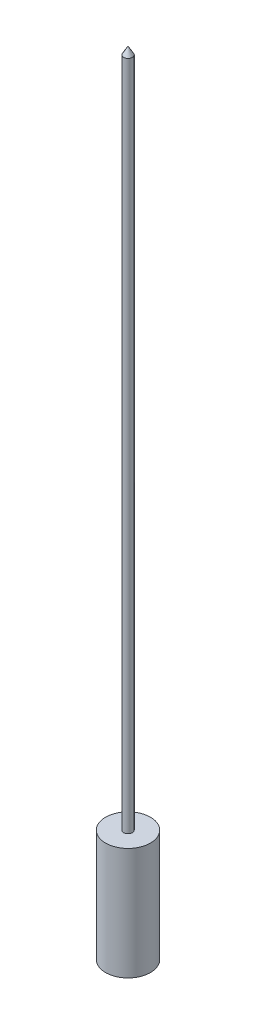
SolidWorks part; units mm, degrees
ref_plane "Front Plane" through (0, 0, 0) normal (0, 0, 1) x (1, 0, 0)
ref_plane "Top Plane" through (0, 0, 0) normal (0, 1, 0) x (1, 0, 0)
ref_plane "Right Plane" through (0, 0, 0) normal (1, 0, 0) x (0, 0, -1)
sketch "Sketch2" plane through (0, 0, 0) normal (1, 0, 0) x (0, 0, -1)
  line L0 (0, 0) -> (0, 76)
  line L1 (0, 76) -> (0, 76.866)
  line L2 (0, 0) -> (0.5, 0)
  line L3 (0.5, 0) -> (0.5, 76)
  line L4 (0.5, 76) -> (0, 76)
  line L5 (0, 76.866) -> (0.5, 76)
  dimension "D1" = 76
  dimension "D2" = 0.5
  dimension "D3" = 30
revolve "Revolve1" add sketch "Sketch2" angle 360 about L0
sketch "Sketch3" plane through (0, 0, 0) normal (0, -1, 0) x (-1, 0, 0)
  circle A0 centre (0, 0) radius 2.54
  dimension "D1" = 5.08
extrude "Boss-Extrude2" add sketch "Sketch3" along normal blind 12.7
